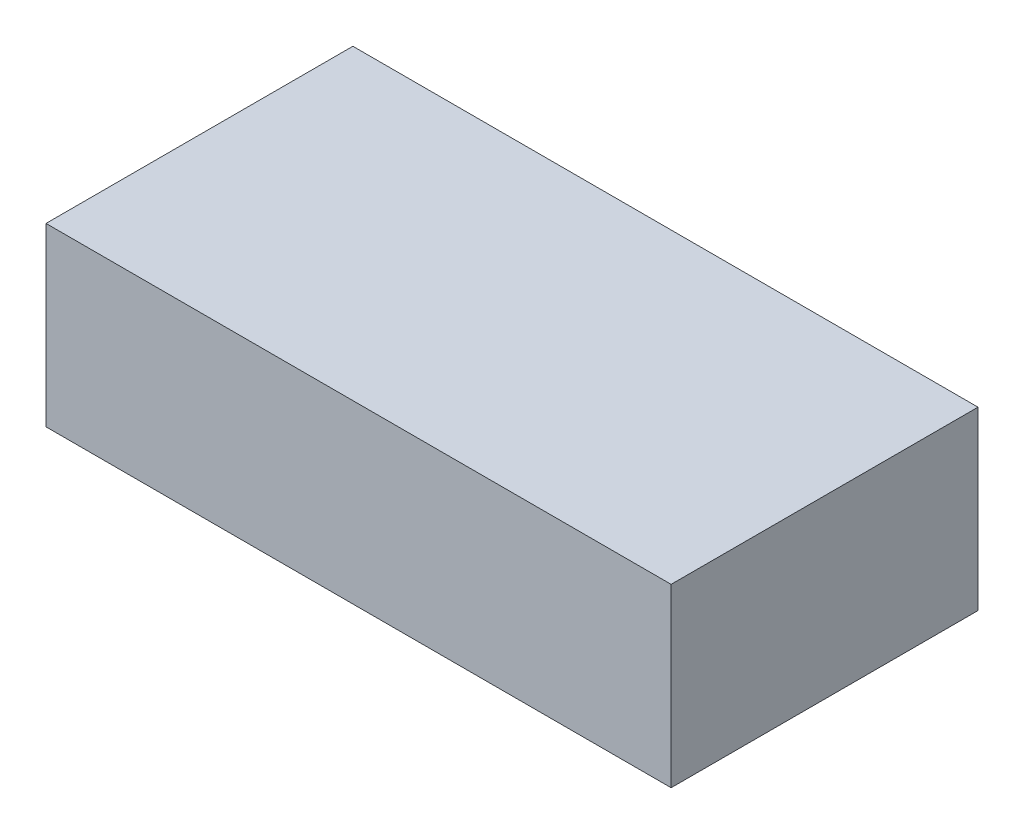
SolidWorks part; units mm, degrees
ref_plane "Płaszczyzna przednia" through (0, 0, 0) normal (0, 0, 1) x (1, 0, 0)
ref_plane "Płaszczyzna górna" through (0, 0, 0) normal (0, 1, 0) x (1, 0, 0)
ref_plane "Płaszczyzna prawa" through (0, 0, 0) normal (1, 0, 0) x (0, 0, -1)
sketch "Szkic1" plane through (0, 0, 0) normal (0, 1, 0) x (1, 0, 0)
  line L1 (-110, -54) -> (110, -54)
  line L2 (-110, -54) -> (-110, 54)
  line L3 (-110, 54) -> (110, 54)
  line L4 (110, -54) -> (110, 54)
  line L5 (-110, -54) -> (110, 54) construction
  line L6 (-110, 54) -> (110, -54) construction
  point P0 (0, 0)
  dimension "D1" = 220
  dimension "D2" = 108
extrude "Dodanie-wyciągnięcie1" add sketch "Szkic1" along normal blind 62
sketch "Szkic2" plane through (-110, 0, 0) normal (-1, 0, 0) x (0, 0, 1)
  line L0 (-54, 62) -> (-54, 0) construction
  line L1 (-49, 37) -> (-24.3, 37)
  line L2 (-49, 37) -> (-49, 57)
  line L3 (-49, 57) -> (-24.3, 57)
  line L4 (-24.3, 37) -> (-24.3, 57)
  line L5 (-49, 37) -> (-24.3, 57) construction
  line L6 (-49, 57) -> (-24.3, 37) construction
  line L7 (-54, 62) -> (54, 62) construction
  line L8 (54, 62) -> (54, 0) construction
  line L9 (-3, 6) -> (47, 6)
  line L10 (-3, 6) -> (-3, 56)
  line L11 (-3, 56) -> (47, 56)
  line L12 (47, 6) -> (47, 56)
  line L13 (-3, 6) -> (47, 56) construction
  line L14 (-3, 56) -> (47, 6) construction
  point P0 (-36.65, 47)
  point P10 (22, 31)
  point P16 (54, 31)
  dimension "D1" = 24.7
  dimension "D2" = 20
  dimension "D3" = 5
  dimension "D4" = 5
  dimension "D5" = 50
  dimension "D6" = 50
  dimension "D7" = 7
extrude "Dodanie-wyciągnięcie2" add sketch "Szkic2" along normal blind 0.5
